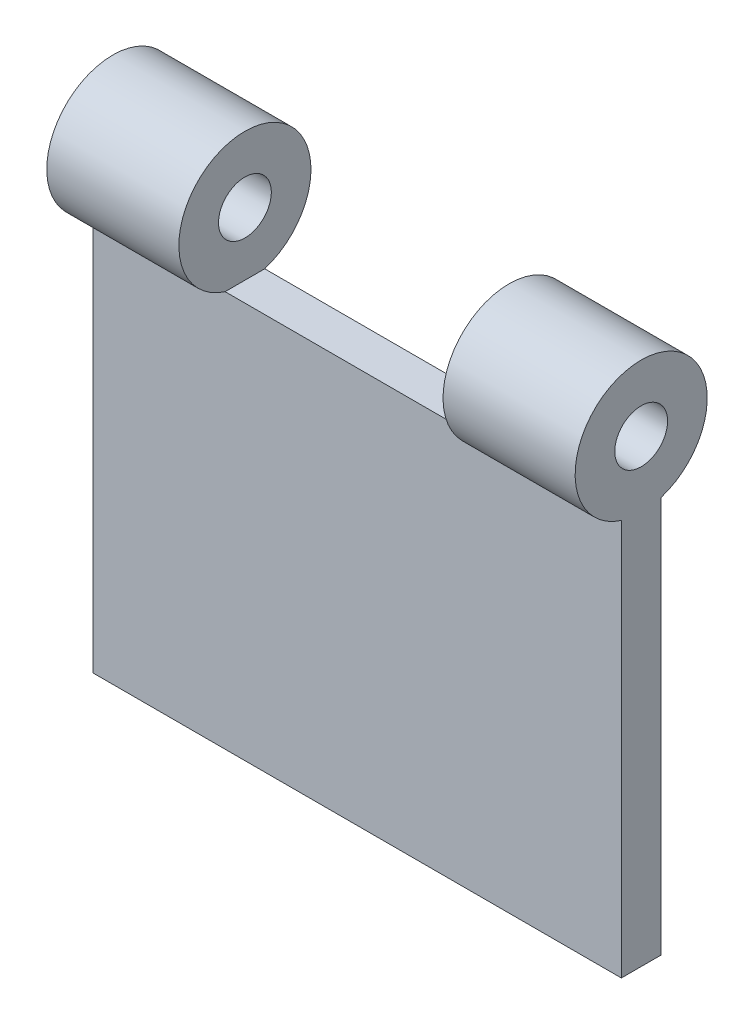
SolidWorks part; units mm, degrees
ref_plane "Front Plane" through (0, 0, 0) normal (0, 0, 1) x (1, 0, 0)
ref_plane "Top Plane" through (0, 0, 0) normal (0, 1, 0) x (1, 0, 0)
ref_plane "Right Plane" through (0, 0, 0) normal (1, 0, 0) x (0, 0, -1)
sketch "Sketch2" plane through (0, 0, 0) normal (1, 0, 0) x (0, 0, -1)
  line L0 (0, 55) -> (0, -55) construction
  line L3 (-1.5, 21.9186) -> (-1.5, -8.0814)
  line L4 (-1.5, -8.0814) -> (1.5, -8.0814)
  line L5 (1.5, 21.9186) -> (1.5, -8.0814)
  arc A0 (1.5, 21.9186) -> (-1.5, 21.9186) centre (0, 26.6883) ccw
  circle A1 centre (0, 26.6883) radius 2
  dimension "D3" = 10
  dimension "D4" = 4
  dimension "D1" = 1.5
  dimension "D2" = 1.5
  dimension "D5" = 30
extrude "Boss-Extrude1" add sketch "Sketch2" along normal mid plane 40
sketch "Sketch3" plane through (0, 0, 0) normal (1, 0, 0) x (0, 0, -1)
  line L0 (1.5, 21.9186) -> (-1.5, 21.9186)
  circle A0 centre (0, 26.6883) radius 2 construction
  arc A1 (1.5, 21.9186) -> (-1.5, 21.9186) centre (0, 26.6883) ccw construction
  circle A2 centre (0, 26.6883) radius 2
  arc A3 (1.5, 21.9186) -> (-1.5, 21.9186) centre (0, 26.6883) ccw
extrude "Cut-Extrude1" cut sketch "Sketch3" against normal mid plane 20
